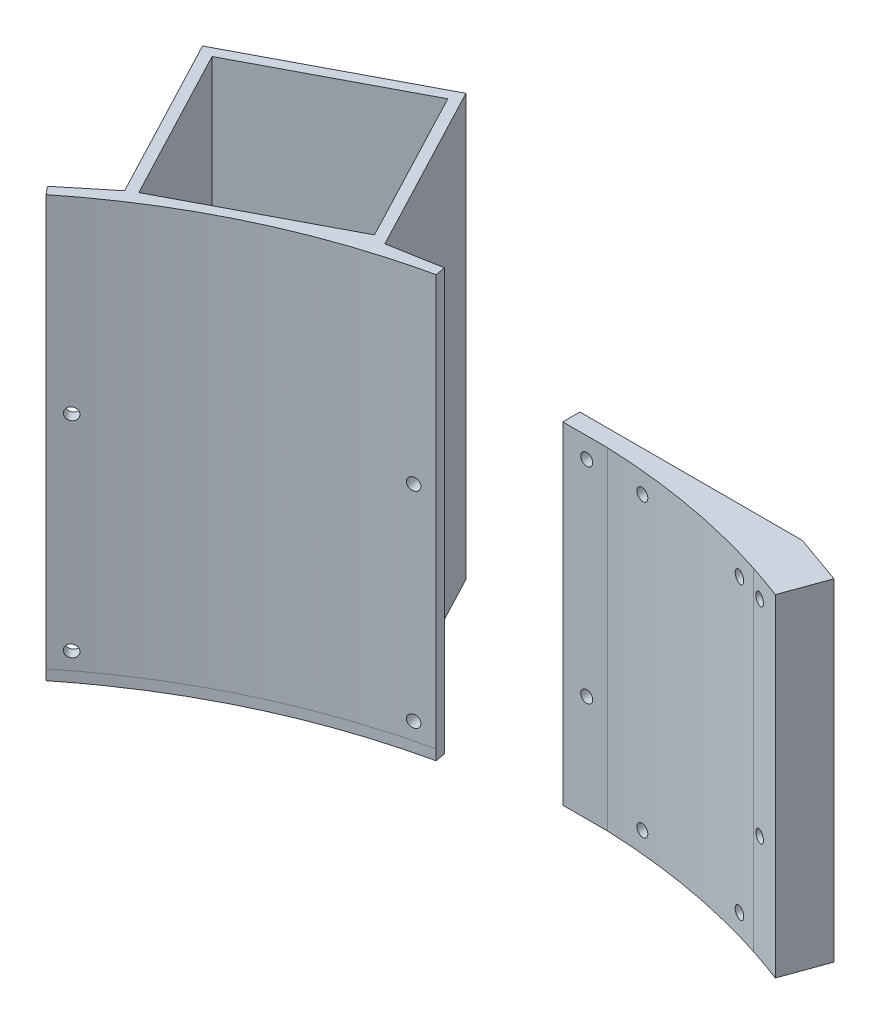
SolidWorks part; units mm, degrees
ref_plane "Front Plane" through (0, 0, 0) normal (0, 0, 1) x (1, 0, 0)
ref_plane "Top Plane" through (0, 0, 0) normal (0, 1, 0) x (1, 0, 0)
ref_plane "Right Plane" through (0, 0, 0) normal (1, 0, 0) x (0, 0, -1)
sketch "Sketch2" plane through (0, 0, 0) normal (0, 1, 0) x (1, 0, 0)
  line L0 (-120, 144.0703) -> (120, 144.0703) construction
  line L2 (6, 187.5) -> (58, 187.5) construction
  line L3 (58, 187.5) -> (58, 302.5) construction
  line L8 (58, 302.5) -> (0, 302.5) construction
  line L9 (0, 302.5) -> (0, 228.1791) construction
  line L10 (0, 228.1791) -> (58, 228.1791) construction
  line L11 (0, 144.0703) -> (0, 334.8408) construction
  line L12 (-103.9561, 160.572) -> (-58.8111, 184.2981)
  line L13 (-58.8111, 184.2981) -> (-82.5372, 229.4431)
  line L14 (-82.5372, 229.4431) -> (-127.6822, 205.717)
  line L15 (-127.6822, 205.717) -> (-103.9561, 160.572)
  line L16 (-131.7335, 206.9769) -> (-106.4972, 158.9585)
  line L18 (-55.0298, 183.5519) -> (-81.2773, 233.4944)
  line L19 (-81.2773, 233.4944) -> (-131.7335, 206.9769)
  line L20 (-112.7821, 149.7787) -> (-108.9573, 144.6919) construction
  line L22 (-106.4972, 158.9585) -> (-118.8937, 148.8428)
  line L24 (-39.7359, 183.2411) -> (-40.2644, 186.1942)
  line L25 (-40.2644, 186.1942) -> (-55.0298, 183.5519)
  line L26 (-45.0511, 181.9892) -> (-43.8477, 177.1748) construction
  line L27 (-118.8937, 148.8428) -> (-116.997, 146.5185)
  line L28 (-101.7471, 158.3439) -> (-59.0456, 180.7858) construction
  line L29 (-112.7821, 149.7787) -> (-45.0511, 181.9892) construction
  line L32 (7.4972, 192.5) -> (58, 192.5)
  line L34 (7.4972, 192.5) -> (-7, 192.5)
  line L35 (-7, 192.5) -> (-7, 187.5)
  line L36 (-7, 187.5) -> (6, 187.5)
  line L37 (62.7337, 176.6939) -> (67.1159, 189.0366) construction
  line L38 (58, 192.5) -> (72.1308, 187.483)
  line L39 (62.7337, 176.6939) -> (53.0987, 180.0309) construction
  line L40 (72.3298, 187.411) -> (67.7777, 174.8211)
  line L41 (72.1308, 187.483) -> (72.3298, 187.411)
  arc A0 (120, 144.0703) -> (-116.9975, 146.5191) centre (0, 0) ccw construction
  spline S0 degree 3 poles (-116.997, 146.5185) (-94.2105, 164.6441) (-68.4568, 176.885) (-39.7359, 183.2411) knots 0.004466 0.004466 0.004466 0.004466 1 1 1 1
  spline S1 degree 2 poles (6, 187.5) (32.6742, 186.4915) (58, 178.3038) knots 0 0 0 1 1 1
  spline S2 degree 2 poles (58, 178.3038) (62.9372, 176.6978) (67.7777, 174.8211) knots 0 0 0 1 1 1
  point P40 (0, 0)
  dimension "D1" = 375
  dimension "D2" = 240
  dimension "D3" = 52
  dimension "D4" = 115
  dimension "D5" = 58
  dimension "D6" = 51
  dimension "D7" = 51
  dimension "D8" = 3
  dimension "D9" = 16
  dimension "D10" = 3
  dimension "D11" = 3
  dimension "D12" = 3
  dimension "D13" = 3
  dimension "D14" = 75
  dimension "D15" = 3
  dimension "D16" = 15
  dimension "D17" = 90
  dimension "D18" = 5
  dimension "D19" = 7
  dimension "D20" = 5
  dimension "D21" = 5.25
extrude "Boss-Extrude1" add sketch "Sketch2" along normal blind 120
sketch "Sketch4" plane through (-120.4321, 0, -147.5875) normal (-0.6322, 0, -0.7748) x (-0.7748, 0, 0.6322)
  line L0 (-7.3124, 0) -> (-7.3124, 65) construction
  line L1 (-1.9856, 0) -> (-85.0632, 0) construction
  circle A0 centre (-7.3124, 5) radius 1.75
  circle A1 centre (-7.3124, 65) radius 1.75
  point P0 (-7.3124, 0)
  point P10 (20.9641, 64.3086)
  dimension "D1" = 3.5
  dimension "D3" = 3.5
  dimension "D2" = 5
  dimension "D4" = 60
sketch "Sketch5" plane through (0, 0, 0) normal (0, -1, 0) x (1, 0, 0)
  line L0 (-39.7359, -183.2411) -> (-40.2644, -186.1942) construction
  line L1 (-40.2644, -186.1942) -> (-55.0298, -183.5519) construction
  line L2 (-55.0298, -183.5519) -> (-81.2773, -233.4944) construction
  line L3 (-81.2773, -233.4944) -> (-131.7335, -206.9769) construction
  line L4 (-131.7335, -206.9769) -> (-106.4972, -158.9585) construction
  line L5 (-106.4972, -158.9585) -> (-118.8937, -148.8428) construction
  line L6 (-118.8937, -148.8428) -> (-116.997, -146.5185) construction
  line L7 (-39.7359, -183.2411) -> (-40.2644, -186.1942)
  line L8 (-40.2644, -186.1942) -> (-55.0298, -183.5519)
  line L9 (-55.0298, -183.5519) -> (-81.2773, -233.4944)
  line L10 (-81.2773, -233.4944) -> (-131.7335, -206.9769)
  line L11 (-131.7335, -206.9769) -> (-106.4972, -158.9585)
  line L12 (-106.4972, -158.9585) -> (-118.8937, -148.8428)
  line L13 (-118.8937, -148.8428) -> (-116.997, -146.5185)
  parabola Q0 (-116.997, -146.5185) -> (-39.7359, -183.2411) focus (-42.8303, -84.8191) apex (-84.4676, -167.3955) construction
  parabola Q1 (-116.997, -146.5185) -> (-39.7359, -183.2411) focus (-42.8303, -84.8191) apex (-84.4676, -167.3955)
extrude "Boss-Extrude2" add sketch "Sketch5" along normal blind 3
extrude "Cut-Extrude1" cut sketch "Sketch4" against normal blind 10
sketch "Sketch6" plane through (-33.5359, 0, -187.3983) normal (-0.1762, 0, -0.9844) x (-0.9844, 0, 0.1762)
  line L0 (12.288, 0) -> (12.288, 65) construction
  circle A0 centre (12.288, 65) radius 1.75
  circle A2 centre (12.288, 5) radius 1.75
  point P0 (12.288, 0)
  dimension "D1" = 60
  dimension "3.5" = 3.5
  dimension "D2" = 3.5
  dimension "D3" = 5
extrude "Cut-Extrude2" cut sketch "Sketch6" against normal blind 10
sketch "Sketch7" plane through (0, 0, -192.5) normal (0, 0, -1) x (-1, 0, 0)
  line L0 (-58, 120) -> (-58, 0) construction
  line L1 (-7.4972, 0) -> (-58, 0) construction
  line L2 (-58, 48.5) -> (-23.134, 48.5) construction
  line L3 (-58, 97) -> (7, 97)
  line L4 (7, 120) -> (7, 0) construction
  line L5 (7, 97) -> (7, 120)
  line L6 (7, 120) -> (-58, 120)
  line L7 (-58, 120) -> (-58, 97)
  circle A0 centre (-17, 6) radius 1.75
  circle A1 centre (-52, 6) radius 1.75
  circle A2 centre (-17, 91) radius 1.75
  circle A3 centre (-52, 91) radius 1.75
  circle A4 centre (0, 31) radius 1.75
  circle A5 centre (0, 91) radius 1.75
  point P26 (0, 0)
  dimension "D1" = 3.5
  dimension "D2" = 3.5
  dimension "D9" = 3.5
  dimension "D10" = 3.5
  dimension "D3" = 35
  dimension "D4" = 6
  dimension "D5" = 6
  dimension "D6" = 6
  dimension "D7" = 42.5
  dimension "D8" = 6
  dimension "D11" = 60
  dimension "D12" = 7
  dimension "D13" = 6
  dimension "D14" = 7
extrude "Cut-Extrude3" cut sketch "Sketch7" against normal blind 20
sketch "Sketch8" plane through (67.1874, 0, -189.2381) normal (0.3346, 0, -0.9424) x (-0.9424, 0, -0.3346)
  line L1 (2.2493, 91) -> (2.2493, 31) construction
  line L2 (9.7493, 97) -> (9.7493, 0) construction
  line L3 (9.7493, 97) -> (-5.2456, 97)
  line L4 (-5.2456, 120) -> (-5.2456, 0) construction
  line L6 (-5.2456, 120) -> (9.7493, 120)
  line L7 (9.7493, 120) -> (9.7493, 97)
  line L8 (-5.2456, 120) -> (-14.1393, 120)
  line L9 (-14.1393, 120) -> (-14.1393, 97)
  line L10 (-14.1393, 97) -> (-5.2456, 97)
  circle A0 centre (2.2493, 31) radius 1.75
  circle A1 centre (2.2493, 91) radius 1.75
  dimension "D1" = 3.5
  dimension "D3" = 3.5
  dimension "D2" = 6
  dimension "D4" = 60
  dimension "D5" = 7.5
extrude "Cut-Extrude4" cut sketch "Sketch8" against normal blind 20
